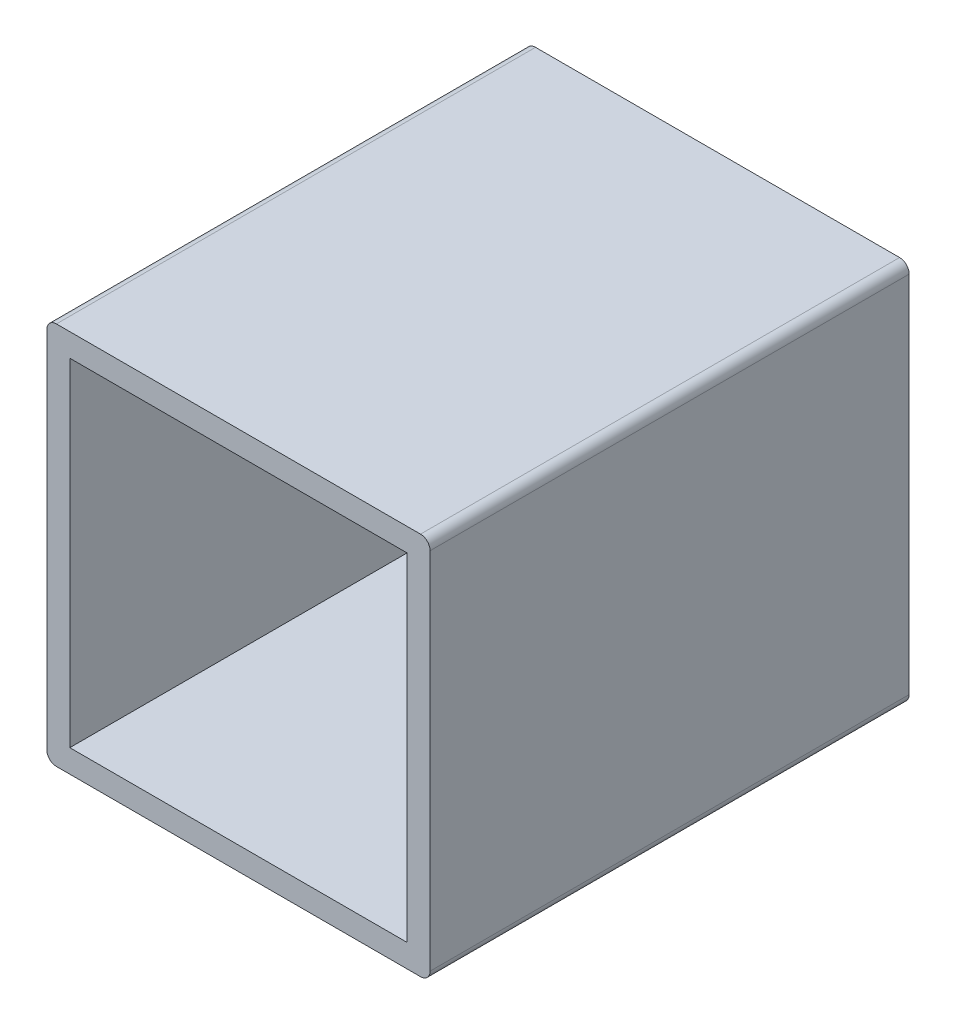
SolidWorks part; units mm, degrees
material "AISI 1020"
ref_plane "Plano frontal" through (0, 0, 0) normal (0, 0, 1) x (1, 0, 0)
ref_plane "Plano superior" through (0, 0, 0) normal (0, 1, 0) x (1, 0, 0)
ref_plane "Plano direito" through (0, 0, 0) normal (1, 0, 0) x (0, 0, -1)
sketch "Esboço1" plane through (0, 0, 0) normal (0, 0, 1) x (1, 0, 0)
  line L0 (-35.2, 35.2) -> (35.2, 35.2)
  line L1 (-38, -40) -> (38, -40)
  line L2 (-40, -38) -> (-40, 38)
  line L3 (-38, 40) -> (38, 40)
  line L4 (40, -38) -> (40, 38)
  line L5 (-40, -40) -> (40, 40) construction
  line L6 (-40, 40) -> (40, -40) construction
  line L7 (35.2, -35.2) -> (35.2, 35.2)
  line L8 (-35.2, -35.2) -> (35.2, -35.2)
  line L9 (-35.2, -35.2) -> (-35.2, 35.2)
  arc A0 (-40, -38) -> (-38, -40) centre (-38, -38) ccw
  arc A1 (38, -40) -> (40, -38) centre (38, -38) ccw
  arc A2 (38, 40) -> (40, 38) centre (38, 38) cw
  arc A3 (-38, 40) -> (-40, 38) centre (-38, 38) ccw
  arc A4 (35.2, 35.2) -> (35.2, 35.2) centre (35.2, 35.2) cw
  arc A5 (35.2, -35.2) -> (35.2, -35.2) centre (35.2, -35.2) ccw
  arc A6 (-35.2, -35.2) -> (-35.2, -35.2) centre (-35.2, -35.2) ccw
  arc A7 (-35.2, 35.2) -> (-35.2, 35.2) centre (-35.2, 35.2) ccw
  point P0 (0, 0)
  dimension "D3" = 2
  dimension "D1" = 80
  dimension "D2" = 80
  dimension "D4" = 4.8
extrude "Ressalto-extrusão1" add sketch "Esboço1" against normal mid plane 100
